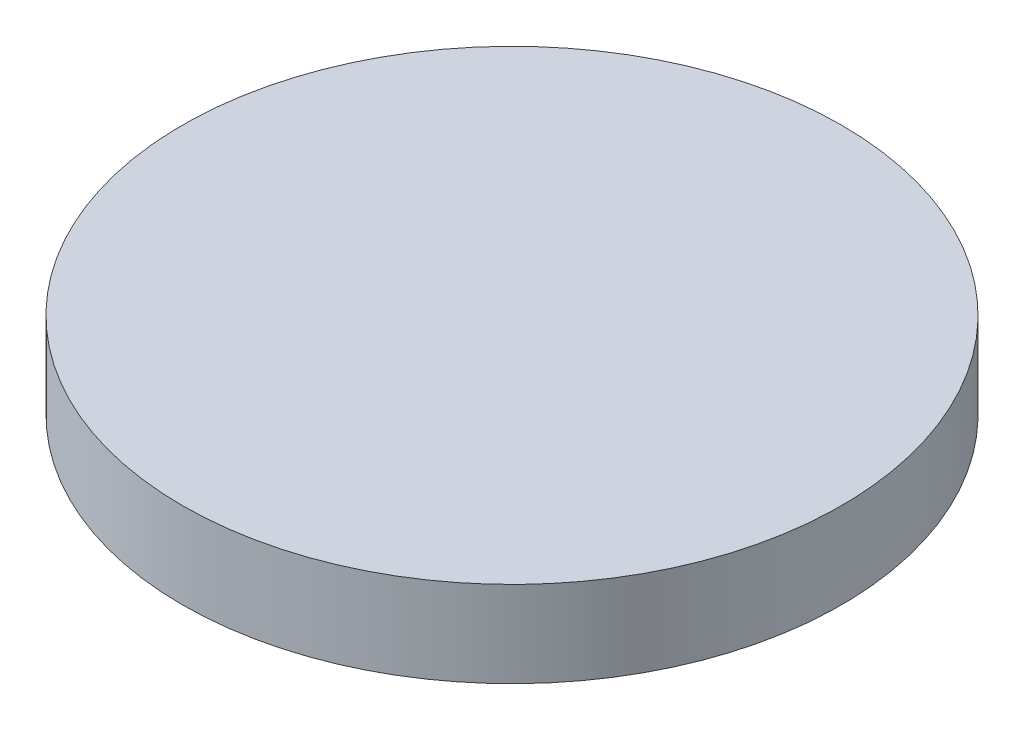
SolidWorks part; units mm, degrees
ref_plane "Front Plane" through (0, 0, 0) normal (0, 0, 1) x (1, 0, 0)
ref_plane "Top Plane" through (0, 0, 0) normal (0, 1, 0) x (1, 0, 0)
ref_plane "Right Plane" through (0, 0, 0) normal (1, 0, 0) x (0, 0, -1)
sketch "Sketch1" plane through (0, 0, 0) normal (0, 1, 0) x (1, 0, 0)
  circle A0 centre (0, 0) radius 11.5
  dimension "D1" = 23
extrude "Boss-Extrude1" add sketch "Sketch1" along normal mid plane 3
